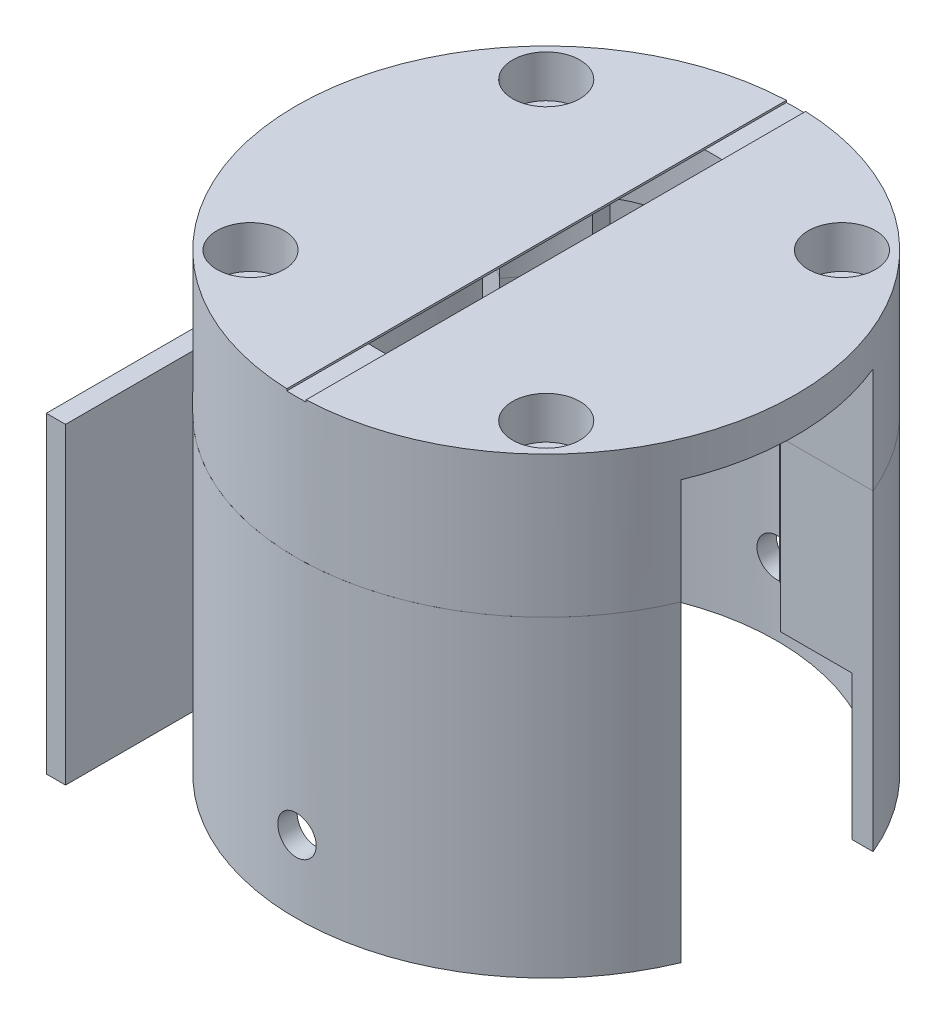
SolidWorks part; units mm, degrees
ref_plane "Front Plane" through (0, 0, 0) normal (0, 0, 1) x (1, 0, 0)
ref_plane "Top Plane" through (0, 0, 0) normal (0, 1, 0) x (1, 0, 0)
ref_plane "Right Plane" through (0, 0, 0) normal (1, 0, 0) x (0, 0, -1)
sketch "Sketch1" plane through (0, 0, 0) normal (0, 1, 0) x (1, 0, 0)
  circle A0 centre (0, 0) radius 26
  dimension "D1" = 52
extrude "Boss-Extrude1" add sketch "Sketch1" along normal blind 47
sketch "Sketch2" plane through (0, 47, 0) normal (0, 1, 0) x (1, 0, 0)
  circle A0 centre (0, 0) radius 17.5
extrude "Cut-Extrude1" cut sketch "Sketch2" against normal blind 32
sketch "Sketch3" plane through (0, 15, 0) normal (0, 1, 0) x (1, 0, 0)
  circle A0 centre (0, 0) radius 24
extrude "Cut-Extrude2" cut sketch "Sketch3" against normal through all
ref_plane "Plane1" through (26, 0, 0) normal (1, 0, 0) x (0, 0, -1)
ref_plane "Plane2" through (0, 32.5, 0) normal (0, 1, 0) x (1, 0, 0)
sketch "Sketch11" plane through (26, 0, 0) normal (1, 0, 0) x (0, 0, -1)
  line L4 (-10, 0) -> (10, 0)
  line L5 (-10, 0) -> (-10, 43.5)
  line L6 (-10, 43.5) -> (10, 43.5)
  line L7 (10, 0) -> (10, 43.5)
  line L8 (-10, 0) -> (10, 43.5) construction
  line L9 (-10, 43.5) -> (10, 0) construction
  point P0 (0, 21.75)
  point P5 (0, 0)
  dimension "D3" = 20
extrude "Cut-Extrude3" cut sketch "Sketch11" against normal blind 15
sketch "Sketch12" plane through (0, 47, 0) normal (0, 1, 0) x (1, 0, 0)
  circle A0 centre (0, 0) radius 26
extrude "Boss-Extrude2" add sketch "Sketch12" along normal blind 0.2
sketch "Sketch26" plane through (0, 0, 0) normal (0, -1, 0) x (1, 0, 0)
  line L1 (-26, 26) -> (-24, 26)
  line L2 (-26, 26) -> (-26, -26)
  line L3 (-26, -26) -> (-24, -26)
  line L4 (-24, 26) -> (-24, -26)
  dimension "D1" = 2
sketch "Sketch32" plane through (26, 0, 0) normal (1, 0, 0) x (0, 0, -1)
  line L0 (-26, 0) -> (26, 0) construction
  point P0 (0, 7.5)
  dimension "D1" = 7.5
extrude "Boss-Extrude4" add sketch "Sketch26" against normal blind 32.5
hole_wizard "Ø4.0mm Dowel Hole1" positions "Sketch32" profile "Sketch5" hole size "Ø4.0" standard "ISO"
sketch "Sketch5" plane through (26, 7.5, 0) normal (0, 1, 0) x (0, 0, -1)
  line L0 (0, 0) -> (0, 53.2017)
  line L1 (0, 53.2017) -> (2, 52)
  line L2 (2, 52) -> (2, 0)
  line L5 (2, 0) -> (0, 0)
  line L10 (0, 53.2017) -> (-2, 52) construction
  line L11 (0, -6.35) -> (0, 107.95) construction
  dimension "Hole Dia." = 4
  dimension "Hole Depth" = 52
  dimension "Drill Angle" = 118
pattern_circular "CirPattern1" count 4 over 360 about axis through (0, 0, 0) along (0, 1, 0) of "Ø4.0mm Dowel Hole1"
sketch "Sketch35" plane through (0, 0, 0) normal (0, 0, 1) x (1, 0, 0)
  line L6 (-1, 47.2) -> (1, 47.2)
  line L7 (26, 47.2) -> (-26, 47.2) construction
  line L8 (1, 47.2) -> (1, 47)
  line L9 (1, 47) -> (-1, 47)
  line L12 (0, -25.85) -> (0, 25.85) construction
  line L13 (-1, 47.2) -> (-1, 47)
  point P15 (0, 47)
  point P16 (0, 47.2)
  dimension "D1" = 2
  dimension "D2" = 2
  dimension "D3" = 0.2
extrude "Cut-Extrude5" cut sketch "Sketch35" against normal through all both and the other way through all
sketch "Sketch36" plane through (0, 47.2, 0) normal (0, 1, 0) x (1, 0, 0)
  line L0 (0, 0) -> (-15.3796, 15.3796)
  line L2 (-1, 25.9808) -> (-1, 17.4714) construction
  dimension "D1" = 21.75
  dimension "D2" = 45
hole_wizard "CBORE for M4 Hex Socket Head Cap Screw2" positions "Sketch42" profile "Sketch38" counterbore size "M4" standard "ISO" end condition through all
sketch "Sketch42" plane through (0, 47.2, 0) normal (0, 1, 0) x (1, 0, 0)
  point P0 (-15.3796, 15.3796)
sketch "Sketch38" plane through (-15.3796, 47.2, -15.3796) normal (1, 0, 0) x (0, 0, 1)
  line L0 (0, 0) -> (0, 47.2)
  line L1 (0, 47.2) -> (2, 47.2)
  line L3 (2, 47.2) -> (2, 4.4)
  line L4 (2, 4.4) -> (3.5, 4.4)
  line L5 (3.5, 4.4) -> (3.5, 0)
  line L7 (3.5, 0) -> (0, 0)
  line L11 (0, -6.35) -> (0, 107.95) construction
  dimension "Thru Hole Dia." = 4
  dimension "Thru Hole Depth" = 47.2
  dimension "C'Bore Dia." = 7
  dimension "C'Bore Depth" = 4.4
pattern_circular "CirPattern2" count 4 over 360 about axis through (0, 0, 0) along (0, 1, 0) of "CBORE for M4 Hex Socket Head Cap Screw2"
sketch "Sketch41" plane through (0, 15, 0) normal (0, -1, 0) x (1, 0, 0)
  line L0 (-9.7177, 14.5539) -> (-13.3272, 19.9596)
  line L1 (9.7177, 14.5539) -> (13.3272, 19.9596)
  line L2 (-9.7178, -14.5538) -> (-13.3273, -19.9595)
  line L3 (-14.5539, -9.7177) -> (-19.9596, -13.3272)
  line L4 (9.7177, -14.5539) -> (13.3272, -19.9596)
  line L5 (-14.5539, 9.7177) -> (-19.9596, 13.3272)
  arc A1 (21.8174, 10) -> (21.8174, -10) centre (0, 0) ccw construction
  arc A5 (21.8174, 10) -> (21.8174, -10) centre (0, 0) ccw construction
  arc A6 (-9.7178, -14.5538) -> (9.7177, -14.5539) centre (0, 0) ccw
  arc A7 (-13.3273, -19.9595) -> (13.3272, -19.9596) centre (0, 0) ccw
  arc A8 (-19.9596, 13.3272) -> (-19.9596, -13.3272) centre (0, 0) ccw
  arc A9 (-14.5539, 9.7177) -> (-14.5539, -9.7177) centre (0, 0) ccw
  arc A10 (9.7177, 14.5539) -> (-9.7177, 14.5539) centre (0, 0) ccw
  arc A11 (13.3272, 19.9596) -> (-13.3272, 19.9596) centre (0, 0) ccw
extrude "Cut-Extrude6" cut sketch "Sketch41" against normal blind 25
split "Split2" trim tools "Plane2" bodies to split 136 135 resulting bodies 137 138
